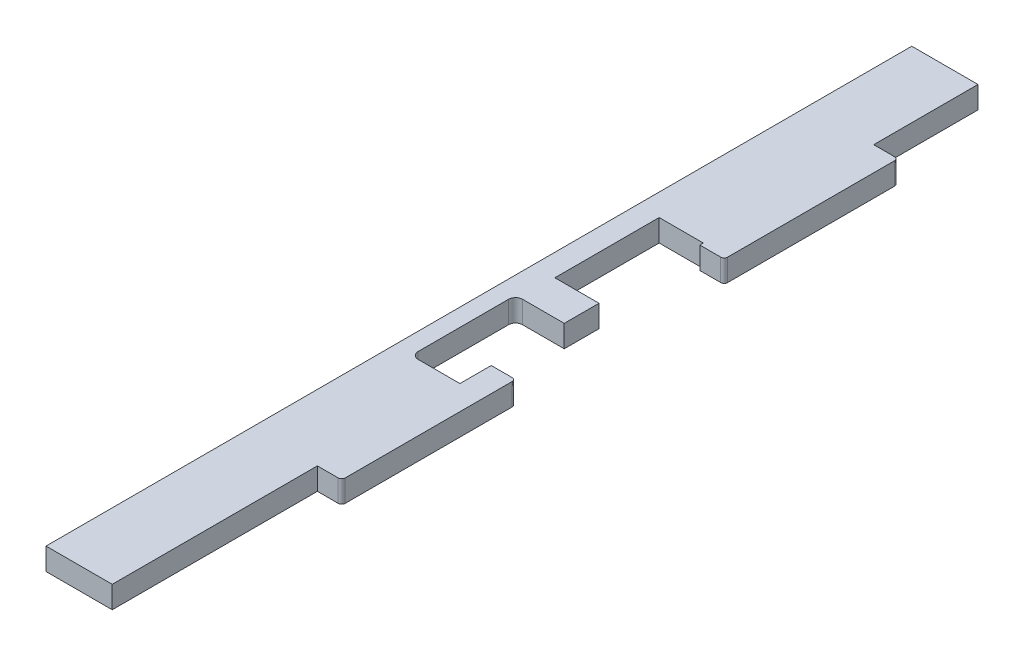
SolidWorks part; units mm, degrees
material "Balsa"
ref_plane "Front Plane" through (0, 0, 0) normal (0, 0, 1) x (1, 0, 0)
ref_plane "Top Plane" through (0, 0, 0) normal (0, 1, 0) x (1, 0, 0)
ref_plane "Right Plane" through (0, 0, 0) normal (1, 0, 0) x (0, 0, -1)
sketch "Sketch2" plane through (0, 0, 0) normal (0, 1, 0) x (1, 0, 0)
  line L0 (-2.5796, -38.687) -> (16.4704, -38.687)
  line L1 (16.4704, -38.687) -> (16.4704, 20.313)
  line L2 (16.4704, 20.313) -> (22.4704, 20.313)
  line L3 (23.4704, 21.313) -> (23.4704, 69.313)
  line L4 (22.4704, 70.313) -> (16.4704, 70.313)
  line L5 (16.4704, 70.313) -> (16.4704, 130.313)
  line L6 (16.4704, 130.313) -> (22.4704, 130.313)
  line L7 (23.4704, 131.313) -> (23.4704, 179.313)
  line L8 (22.4704, 180.313) -> (16.4704, 180.313)
  line L9 (16.4704, 180.313) -> (16.4704, 210.313)
  line L10 (16.4704, 210.313) -> (-2.5796, 210.313)
  line L11 (-2.5796, 210.313) -> (-2.5796, -38.687)
  arc A0 (22.4704, 20.313) -> (23.4704, 21.313) centre (22.4704, 21.313) ccw
  arc A1 (23.4704, 69.313) -> (22.4704, 70.313) centre (22.4704, 69.313) ccw
  arc A2 (22.4704, 130.313) -> (23.4704, 131.313) centre (22.4704, 131.313) ccw
  arc A3 (23.4704, 179.313) -> (22.4704, 180.313) centre (22.4704, 179.313) ccw
  point P14 (23.4704, 20.313)
  point P17 (23.4704, 70.313)
  point P20 (23.4704, 130.313)
  point P23 (23.4704, 180.313)
  dimension "D8" = 1
  dimension "D1" = 19.05
  dimension "D2" = 59
  dimension "D3" = 249
  dimension "D4" = 50
  dimension "D5" = 60
  dimension "D6" = 50
  dimension "D7" = 7
extrude "Boss-Extrude1" add sketch "Sketch2" along normal blind 6.35
sketch "Sketch3" plane through (0, 6.35, 0) normal (0, 1, 0) x (1, 0, 0)
  line L0 (-2.5796, -38.687) -> (16.4704, -38.687) construction
  line L1 (16.4704, 61.313) -> (4.4704, 61.313)
  line L2 (16.4704, 61.313) -> (16.4704, 91.313)
  line L3 (16.4704, 91.313) -> (4.4704, 91.313)
  line L4 (2.4704, 63.313) -> (2.4704, 89.313)
  arc A0 (4.4704, 61.313) -> (2.4704, 63.313) centre (4.4704, 63.313) cw
  arc A1 (2.4704, 89.313) -> (4.4704, 91.313) centre (4.4704, 89.313) cw
  point P10 (2.4704, 91.313)
  dimension "D4" = 2
  dimension "D1" = 100
  dimension "D2" = 30
  dimension "D3" = 14
extrude "Cut-Extrude1" cut sketch "Sketch3" against normal through all
sketch "Sketch5" plane through (0, 0, 0) normal (0, -1, 0) x (1, 0, 0)
  line L0 (16.4704, -91.313) -> (4.4704, -91.313) construction
  line L1 (16.4704, -101.313) -> (3.7704, -101.313)
  line L2 (16.4704, -101.313) -> (16.4704, -131.313)
  line L3 (16.4704, -131.313) -> (3.7704, -131.313)
  line L4 (3.7704, -101.313) -> (3.7704, -131.313)
  dimension "D1" = 30
  dimension "D2" = 10
  dimension "D3" = 12.7
extrude "Cut-Extrude3" cut sketch "Sketch5" against normal through all
